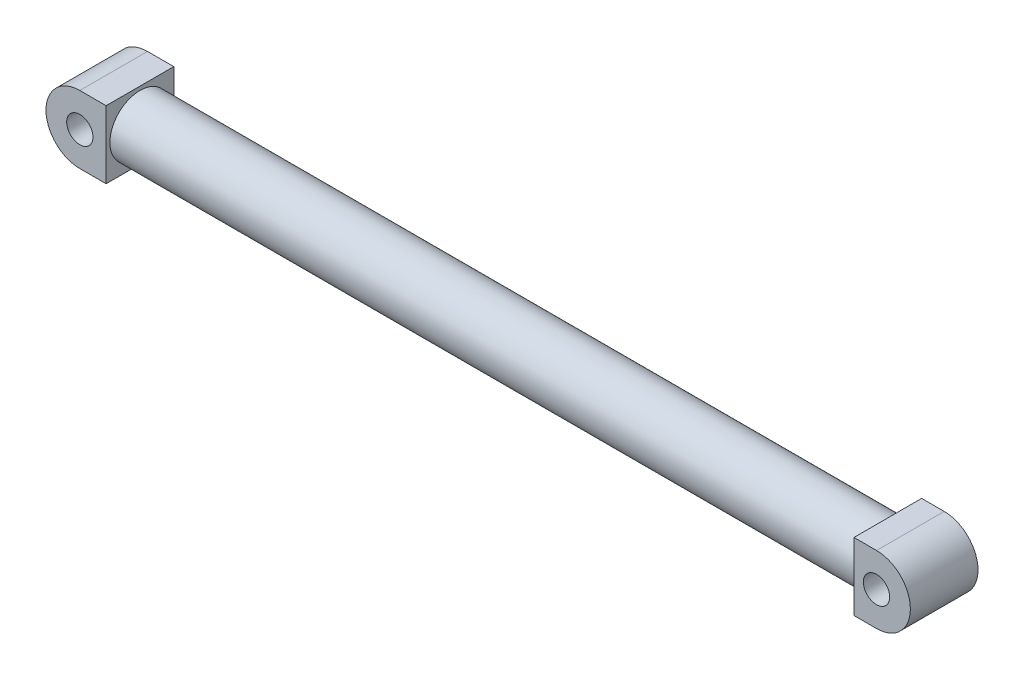
SolidWorks part; units mm, degrees
material "ABS PC"
ref_plane "Front Plane" through (0, 0, 0) normal (0, 0, 1) x (1, 0, 0)
ref_plane "Top Plane" through (0, 0, 0) normal (0, 1, 0) x (1, 0, 0)
ref_plane "Right Plane" through (0, 0, 0) normal (1, 0, 0) x (0, 0, -1)
sketch "Sketch5" plane through (0, 0, 0) normal (0, 0, 1) x (1, 0, 0)
  line L0 (0, 0) -> (106, 0) construction
  line L1 (0, 4.5) -> (106, 4.5)
  line L2 (0, -4.5) -> (106, -4.5)
  arc A0 (0, 4.5) -> (0, -4.5) centre (0, 0) ccw
  arc A1 (106, -4.5) -> (106, 4.5) centre (106, 0) ccw
  circle A2 centre (0, 0) radius 1.75
  circle A3 centre (106, 0) radius 1.75
  point P3 (53, 0)
  dimension "D2" = 4.5
  dimension "D3" = 3.5
  dimension "D4" = 3.5
  dimension "D1" = 106
extrude "Boss-Extrude3" add sketch "Sketch5" along normal blind 9
sketch "Sketch7" plane through (0, 0, 0) normal (1, 0, 0) x (0, 0, -1)
  circle A0 centre (-4.5, 0) radius 4
  circle A1 centre (-4.5, 0) radius 7.5
  dimension "D1" = 8
  dimension "D3" = 15
  dimension "D2" = 4.5
extrude "Cut-Extrude2" cut sketch "Sketch7" along normal blind 99.5 from offset 3.5
